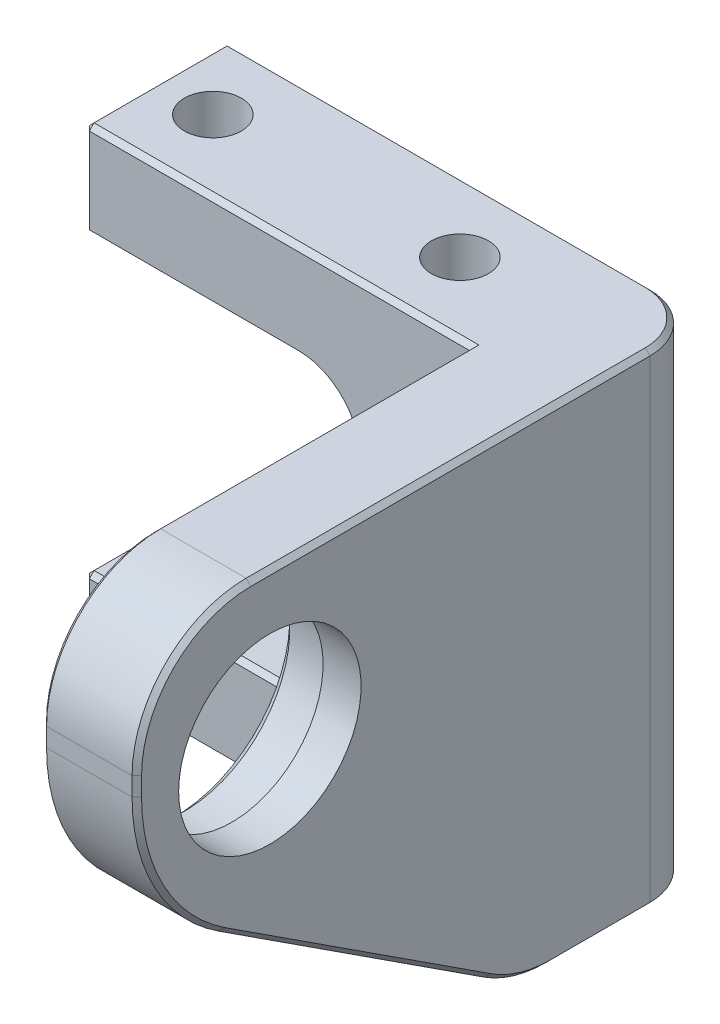
SolidWorks part; units mm, degrees
material "PLA"
ref_plane "Front Plane" through (0, 0, 0) normal (0, 0, 1) x (1, 0, 0)
ref_plane "Top Plane" through (0, 0, 0) normal (0, 1, 0) x (1, 0, 0)
ref_plane "Right Plane" through (0, 0, 0) normal (1, 0, 0) x (0, 0, -1)
sketch "Sketch2" plane through (0, 0, 0) normal (0, 1, 0) x (1, 0, 0)
  line L0 (0, 7.5) -> (50.5, 7.5)
  line L5 (50.5, 7.5) -> (50.5, -52.5)
  line L6 (50.5, -52.5) -> (40.5, -52.5)
  line L7 (40.5, -52.5) -> (40.5, -7.5)
  line L8 (40.5, -7.5) -> (0, -7.5)
  line L9 (0, -7.5) -> (0, 7.5)
  point P5 (0, 0)
  dimension "D1" = 15
  dimension "D2" = 10
  dimension "D3" = 40.5
  dimension "D4" = 45
extrude "Boss-Extrude1" add sketch "Sketch2" along normal blind 50.8 contours L5 L6 L7 L8 L9 L0
sketch "Sketch3" plane through (40.5, 0, 0) normal (-1, 0, 0) x (0, 0, 1)
  line L0 (7.5, 50.8) -> (7.5, 0) construction
  line L1 (52.5, 50.8) -> (7.5, 50.8) construction
  circle A0 centre (38.5, 35.4) radius 11.1
  dimension "D2" = 22.2
  dimension "D1" = 31
  dimension "D3" = 15.4
extrude "Cut-Extrude1" cut sketch "Sketch3" against normal blind 6
sketch "Sketch4" plane through (46.5, 0, 0) normal (-1, 0, 0) x (0, 0, 1)
  circle A2 centre (38.5, 35.4) radius 9.6
  circle A3 centre (38.5, 35.4) radius 9.6
  dimension "D1" = 1.5
extrude "Cut-Extrude2" cut sketch "Sketch4" against normal through all
sketch "Sketch5" plane through (40.5, 0, 0) normal (-1, 0, 0) x (0, 0, 1)
  line L0 (12.5, 0) -> (52.5, 0)
  line L1 (52.5, 0) -> (7.5, 0) construction
  line L2 (52.5, 0) -> (52.5, 26)
  line L3 (52.5, 50.8) -> (52.5, 0) construction
  line L4 (52.5, 26) -> (12.5, 0)
  dimension "D1" = 26
  dimension "D2" = 40
extrude "Cut-Extrude3" cut sketch "Sketch5" against normal through all
fillet "Fillet1" radius 20 1 edges at (45.5, 26, 52.5)
fillet "Fillet2" radius 12 1 edges at (45.5, 50.8, 52.5)
sketch "Sketch6" plane through (0, 50.8, 0) normal (0, 1, 0) x (1, 0, 0)
  line L0 (0, -7.5) -> (0, 7.5) construction
  circle A0 centre (6, 0) radius 3
  circle A1 centre (32, 0) radius 3
  dimension "D1" = 6
  dimension "D2" = 6
  dimension "D3" = 26
extrude "Cut-Extrude4" cut sketch "Sketch6" against normal through all
sketch "Sketch7" plane through (0, 0, 7.5) normal (0, 0, 1) x (1, 0, 0)
  line L0 (0, 50.8) -> (0, 0) construction
  line L1 (0, 40.8) -> (28.5, 40.8)
  line L2 (0, 40.8) -> (0, 10)
  line L3 (0, 10) -> (28.5, 10)
  line L4 (28.5, 40.8) -> (28.5, 10)
  line L5 (40.5, 50.8) -> (0, 50.8) construction
  line L6 (40.5, 20.0848) -> (40.5, 0) construction
  line L7 (40.5, 0) -> (0, 0) construction
  dimension "D1" = 10
  dimension "D2" = 12
  dimension "D3" = 10
extrude "Cut-Extrude5" cut sketch "Sketch7" against normal through all
fillet "Fillet3" radius 6 2 edges at (28.5, 40.8, 0) (28.5, 10, 0)
fillet "Fillet4" radius 6 1 edges at (50.5, 25.4, -7.5)
fillet "Fillet5" radius 12 1 edges at (45.5, 0, 12.5)
chamfer "Chamfer1" distance 0.5 angle 45 38 edges at (11.25, 10, -7.5) (11.25, 40.8, -7.5) (26.7426, 11.7574, -7.5) (26.7426, 39.0426, -7.5) (28.5, 25.4, -7.5) (40.5, 50.8, 24) (11.25, 40.8, 7.5) (40.5, 47.2853, 48.9853) (26.7426, 39.0426, 7.5) (40.5, 37.8269, 52.5) (28.5, 25.4, 7.5) (40.5, 27.3142, 50.0783) (26.7426, 11.7574, 7.5) (0, 5, 7.5) (40.5, 11.0118, 29.4412) (40.5, 0, 8.2214) (20.25, 0, 7.5) (0, 0, 0) (11.25, 10, 7.5) (0, 10, 0) (0, 5, -7.5) (22.25, 0, -7.5) (50.5, 0, 3.7214) (50.5, 11.0118, 29.4412) (50.5, 27.3142, 50.0783) (50.5, 37.8269, 52.5) (50.5, 47.2853, 48.9853) (50.5, 50.8, 19.5) (0, 45.8, -7.5) (22.25, 50.8, -7.5) (0, 50.8, 0) (0, 40.8, 0) (0, 45.8, 7.5) (20.25, 50.8, 7.5) (48.7426, 0, -5.7426) (48.7426, 50.8, -5.7426) (50.5, 0.4949, 12.3533) (40.5, 0.4949, 12.3533)
chamfer "Chamfer2" distance 1 angle 45 1 edges at (40.5, 35.4, 49.6)
mirror "Mirror1" [suppressed]
delete or keep bodies "Body-Delete/Keep 2" [suppressed] type delete bodies bodies 106
